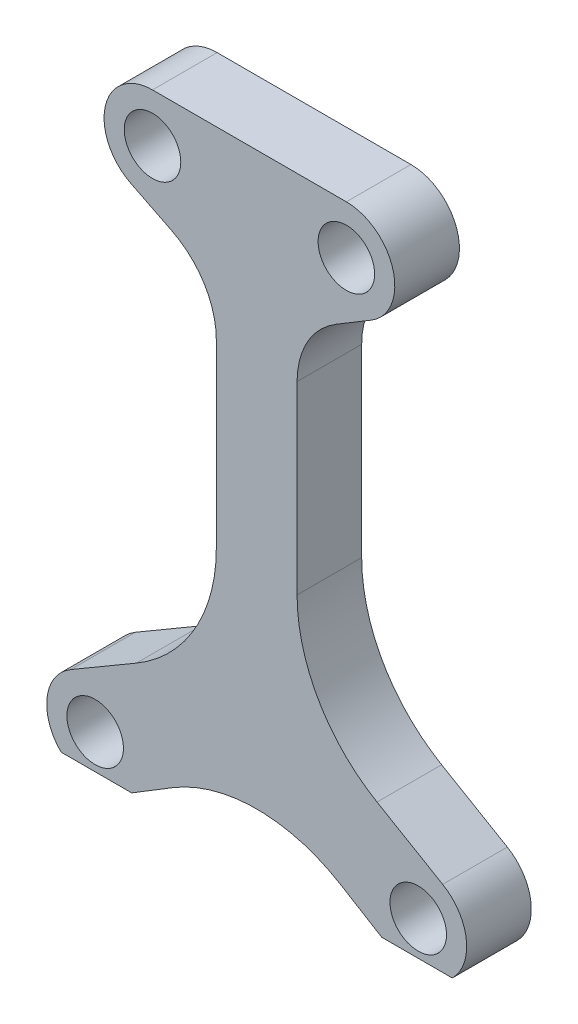
SolidWorks part; units mm, degrees
ref_plane "前视基准面" through (0, 0, 0) normal (0, 0, 1) x (1, 0, 0)
ref_plane "上视基准面" through (0, 0, 0) normal (0, 1, 0) x (1, 0, 0)
ref_plane "右视基准面" through (0, 0, 0) normal (1, 0, 0) x (0, 0, -1)
sketch "草图1" plane through (0, 0, 0) normal (0, 0, 1) x (1, 0, 0)
  line L1 (0, 0) -> (28, 0)
  line L2 (0, 0) -> (0, 40)
  line L3 (0, 40) -> (28, 40)
  line L4 (28, 0) -> (28, 40)
  dimension "D1" = 28
  dimension "D2" = 40
extrude "凸台-拉伸1" add sketch "草图1" along normal blind 4
sketch "草图2" plane through (0, 0, 4) normal (0, 0, 1) x (1, 0, 0)
  circle A0 centre (7.55, 35.3346) radius 1.75
  circle A1 centre (19.55, 35.3346) radius 1.75
  circle A2 centre (4, 2.1346) radius 1.75
  circle A3 centre (24, 2.1346) radius 1.75
  dimension "D1" = 3.5
  dimension "D2" = 3.5
  dimension "D3" = 3.5
  dimension "D4" = 3.5
extrude "切除-拉伸1" cut sketch "草图2" against normal through all
sketch "草图3" plane through (0, 0, 4) normal (0, 0, 1) x (1, 0, 0)
  line L0 (14, 40) -> (14, 0) construction
  line L2 (11.5, 26.9127) -> (11.5, 15.7342)
  line L4 (16.5, 27.1722) -> (16.5, 15.7342)
  line L5 (28, 40) -> (0, 40) construction
  line L6 (0, 0) -> (28, 0) construction
  line L7 (6.2061, 32.6524) -> (8.7398, 31.383)
  line L8 (18.9234, 31.4572) -> (21.096, 32.7636)
  line L9 (6.5511, 7.1036) -> (2.4847, 4.7237)
  line L10 (21.4489, 7.1036) -> (25.5153, 4.7237)
  line L11 (7.55, 38.3346) -> (19.55, 38.3346)
  line L12 (5.563, -0.4261) -> (8.79, 1.5436)
  line L13 (19.21, 1.5436) -> (22.437, -0.4261)
  line L15 (-7.3505, 44.0109) -> (39.4057, 44.0109)
  line L16 (-7.3505, 44.0109) -> (-7.3505, -4.9101)
  line L17 (-7.3505, -4.9101) -> (39.4057, -4.9101)
  line L18 (39.4057, 44.0109) -> (39.4057, -4.9101)
  arc A0 (2.4847, 4.7237) -> (5.563, -0.4261) centre (4, 2.1346) ccw
  arc A1 (22.437, -0.4261) -> (25.5153, 4.7237) centre (24, 2.1346) ccw
  arc A2 (7.55, 38.3346) -> (6.2061, 32.6524) centre (7.55, 35.3346) ccw
  arc A3 (21.096, 32.7636) -> (19.55, 38.3346) centre (19.55, 35.3346) ccw
  arc A4 (8.79, 1.5436) -> (19.21, 1.5436) centre (14, -6.992) cw
  arc A5 (11.5, 15.7342) -> (6.5511, 7.1036) centre (1.5, 15.7342) cw
  arc A6 (21.4489, 7.1036) -> (16.5, 15.7342) centre (26.5, 15.7342) cw
  arc A7 (18.9234, 31.4572) -> (16.5, 27.1722) centre (21.5, 27.1722) ccw
  arc A8 (11.5, 26.9127) -> (8.7398, 31.383) centre (6.5, 26.9127) ccw
  point P32 (14, 4.7237)
  point P39 (16.5, 30)
  point P42 (11.5, 30)
  dimension "D1" = 6
  dimension "D2" = 6
  dimension "D3" = 6
  dimension "D4" = 6
  dimension "D7" = 10
  dimension "D8" = 10
  dimension "D9" = 10
  dimension "D10" = 5
  dimension "D5" = 5
  dimension "D6" = 2.5
extrude "切除-拉伸2" cut sketch "草图3" against normal through all
